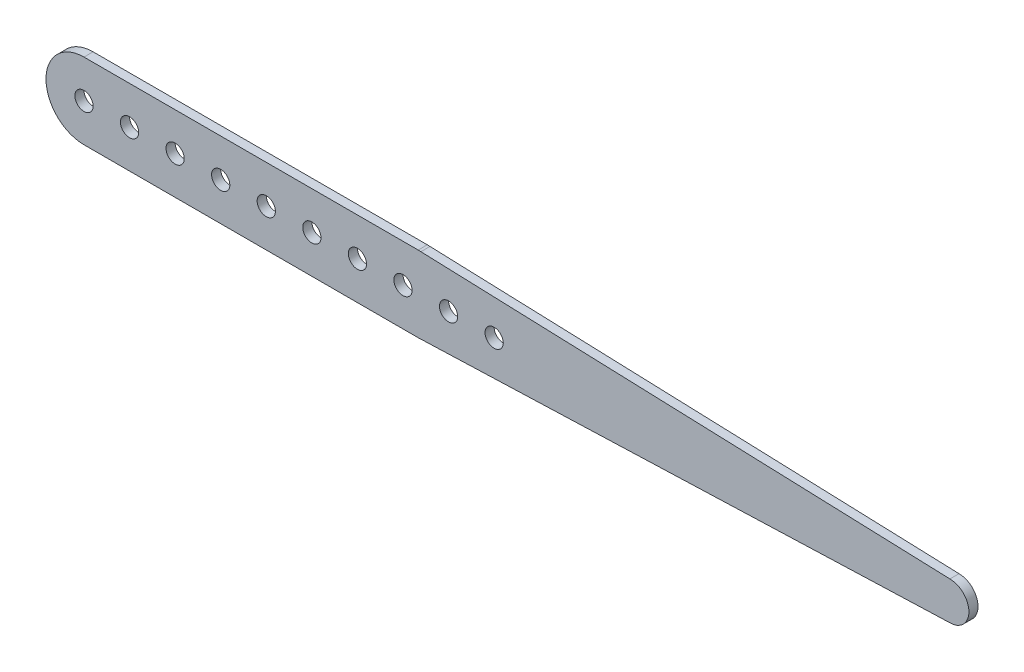
SolidWorks part; units mm, degrees
ref_plane "Front Plane" through (0, 0, 0) normal (0, 0, 1) x (1, 0, 0)
ref_plane "Top Plane" through (0, 0, 0) normal (0, 1, 0) x (1, 0, 0)
ref_plane "Right Plane" through (0, 0, 0) normal (1, 0, 0) x (0, 0, -1)
sketch "Sketch1" plane through (0, 0, 0) normal (0, 0, 1) x (1, 0, 0)
  line L0 (175, 0) -> (350, 0) construction
  line L1 (175.8917, 12.4682) -> (350, 6.25)
  line L2 (350, -6.25) -> (175.8917, -12.4682)
  line L3 (200, 0) -> (65, 0) construction
  line L4 (65, -12.5) -> (175, -12.5)
  line L5 (175, 12.5) -> (65, 12.5)
  arc A2 (350, -6.25) -> (350, 6.25) centre (350, 0) ccw
  arc A7 (175.8917, 12.4682) -> (175, 12.5) centre (175, 0) ccw
  circle A8 centre (65, 0) radius 3
  arc A9 (65, 12.5) -> (65, -12.5) centre (65, 0) ccw
  arc A11 (175, -12.5) -> (175.8917, -12.4682) centre (175, 0) ccw
  circle A12 centre (80, 0) radius 3
  circle A13 centre (95, 0) radius 3
  circle A14 centre (110, 0) radius 3
  circle A15 centre (125, 0) radius 3
  circle A16 centre (140, 0) radius 3
  circle A17 centre (155, 0) radius 3
  circle A18 centre (170, 0) radius 3
  circle A19 centre (185, 0) radius 3
  dimension "D2" = 25
  dimension "D3" = 6.25
  dimension "D6" = 12.5
  dimension "D1" = 175
  dimension "D4" = 9
  dimension "D5" = 25
  dimension "D7" = 110
extrude "Boss-Extrude1" add sketch "Sketch1" along normal blind 3
sketch "Sketch2" plane through (0, 0, 3) normal (0, 0, 1) x (1, 0, 0)
  line L0 (175, 0) -> (200, 0) construction
  circle A0 centre (200, 0) radius 3
extrude "Cut-Extrude1" cut sketch "Sketch2" against normal blind 3
